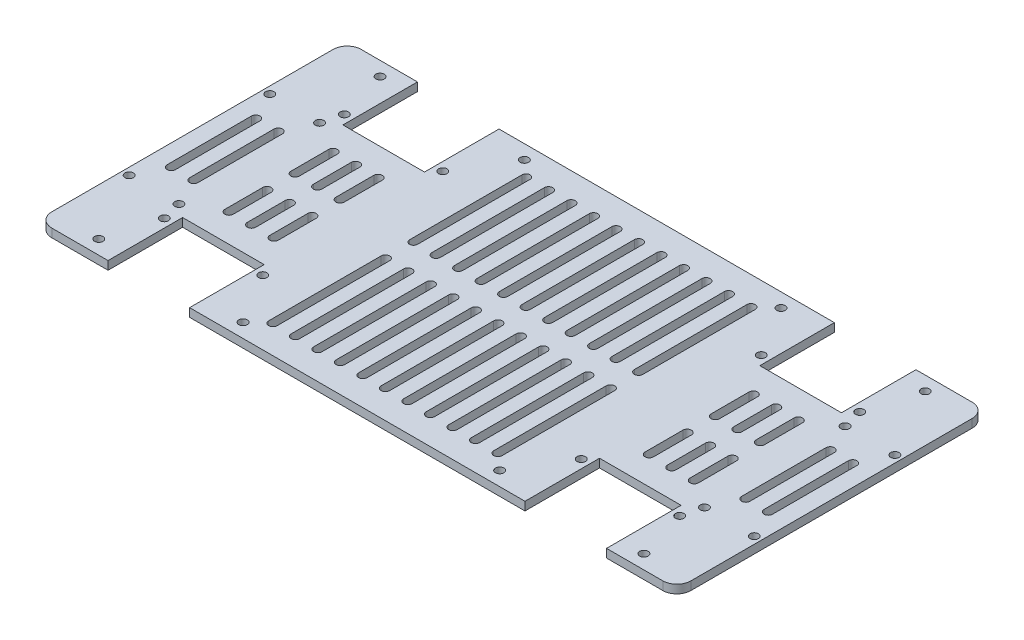
SolidWorks part; units mm, degrees
ref_plane "前视基准面" through (0, 0, 0) normal (0, 0, 1) x (1, 0, 0)
ref_plane "上视基准面" through (0, 0, 0) normal (0, 1, 0) x (1, 0, 0)
ref_plane "右视基准面" through (0, 0, 0) normal (1, 0, 0) x (0, 0, -1)
other "Configuration Table"
sketch "草图1" plane through (0, 0, 0) normal (0, 1, 0) x (1, 0, 0)
  line L5 (-51.0973, -171.2423) -> (-45.0973, -171.2423)
  line L6 (-45.0973, -171.2423) -> (-45.0973, -177.2423)
  line L7 (-45.0973, -177.2423) -> (-51.0973, -177.2423)
  line L8 (-80.0973, -171.2423) -> (-86.0973, -171.2423)
  line L12 (-86.0973, -171.2423) -> (-86.0973, -177.2423)
  line L13 (-86.0973, -177.2423) -> (-80.0973, -177.2423)
  line L14 (-80.0973, -113.2423) -> (-86.0973, -113.2423)
  line L37 (-88.3873, -92.2423) -> (105.4227, -92.2423) construction
  line L38 (105.4227, -92.2423) -> (105.4227, -192.2423) construction
  line L39 (105.4227, -192.2423) -> (-88.3873, -192.2423) construction
  line L40 (-88.3873, -192.2423) -> (-88.3873, -92.2423) construction
  line L42 (-105.0973, -197.2423) -> (122.1327, -197.2423)
  line L43 (122.1327, -197.2423) -> (122.1327, -87.2423)
  line L44 (122.1327, -87.2423) -> (-105.0973, -87.2423)
  line L46 (-105.0973, -87.2423) -> (-105.0973, -197.2423)
  line L48 (-80.0973, -87.2423) -> (-80.0973, -113.7423)
  line L49 (-80.0973, -113.7423) -> (-51.0973, -113.7423)
  line L50 (-51.0973, -113.7423) -> (-51.0973, -87.2423)
  line L52 (-80.0973, -197.2423) -> (-80.0973, -170.7423)
  line L53 (-80.0973, -170.7423) -> (-51.0973, -170.7423)
  line L54 (-51.0973, -170.7423) -> (-51.0973, -197.2423)
  line L56 (97.1327, -87.2423) -> (97.1327, -113.7423)
  line L57 (97.1327, -113.7423) -> (68.1327, -113.7423)
  line L58 (68.1327, -113.7423) -> (68.1327, -87.2423)
  line L60 (68.1327, -197.2423) -> (68.1327, -170.7423)
  line L61 (68.1327, -170.7423) -> (97.1327, -170.7423)
  line L62 (97.1327, -170.7423) -> (97.1327, -197.2423)
  line L63 (-86.0973, -113.2423) -> (-86.0973, -107.2423)
  line L64 (-86.0973, -107.2423) -> (-80.0973, -107.2423)
  line L66 (-51.0973, -107.2423) -> (-45.0973, -107.2423)
  line L67 (-45.0973, -107.2423) -> (-45.0973, -113.2423)
  line L68 (-45.0973, -113.2423) -> (-51.0973, -113.2423)
  line L70 (-86.0973, -110.2423) -> (-80.0973, -110.2423) construction
  line L72 (-83.0973, -107.2423) -> (-83.0973, -113.2423) construction
  line L73 (-51.0973, -110.2423) -> (-45.0973, -110.2423) construction
  line L74 (-48.0973, -107.2423) -> (-48.0973, -113.2423) construction
  line L75 (-86.0973, -174.2423) -> (-80.0973, -174.2423) construction
  line L76 (-83.0973, -171.2423) -> (-83.0973, -177.2423) construction
  line L77 (-48.0973, -171.2423) -> (-48.0973, -177.2423) construction
  line L78 (-45.0973, -174.2423) -> (-51.0973, -174.2423) construction
  line L79 (68.1327, -171.2423) -> (62.1327, -171.2423)
  line L80 (62.1327, -171.2423) -> (62.1327, -177.2423)
  line L81 (62.1327, -177.2423) -> (68.1327, -177.2423)
  line L82 (68.1327, -107.2423) -> (62.1327, -107.2423)
  line L83 (62.1327, -107.2423) -> (62.1327, -113.2423)
  line L84 (62.1327, -113.2423) -> (68.1327, -113.2423)
  line L85 (97.1327, -107.2423) -> (103.1327, -107.2423)
  line L86 (103.1327, -107.2423) -> (103.1327, -113.2423)
  line L87 (103.1327, -113.2423) -> (97.1327, -113.2423)
  line L88 (97.1327, -171.2423) -> (103.1327, -171.2423)
  line L89 (103.1327, -171.2423) -> (103.1327, -177.2423)
  line L90 (103.1327, -177.2423) -> (97.1327, -177.2423)
  line L91 (65.1327, -107.2423) -> (65.1327, -113.2423) construction
  line L92 (62.1327, -110.2423) -> (68.1327, -110.2423) construction
  line L93 (97.1327, -110.2423) -> (103.1327, -110.2423) construction
  line L94 (100.1327, -107.2423) -> (100.1327, -113.2423) construction
  line L95 (62.1327, -174.2423) -> (68.1327, -174.2423) construction
  line L96 (65.1327, -171.2423) -> (65.1327, -177.2423) construction
  line L97 (97.1327, -174.2423) -> (103.1327, -174.2423) construction
  line L98 (100.1327, -171.2423) -> (100.1327, -177.2423) construction
  line L99 (-105.0973, -142.2423) -> (122.1327, -142.2423) construction
  line L100 (8.5177, -87.2423) -> (8.5177, -197.2423) construction
  line L101 (8.5177, -97.2423) -> (8.5177, -137.2423) construction
  line L104 (10.0177, -97.2423) -> (10.0177, -137.2423)
  line L107 (7.0177, -97.2423) -> (7.0177, -137.2423)
  line L110 (8.5177, -147.2423) -> (8.5177, -187.2423) construction
  line L113 (10.0177, -147.2423) -> (10.0177, -187.2423)
  line L114 (7.0177, -147.2423) -> (7.0177, -187.2423)
  line L115 (16.5177, -97.2423) -> (16.5177, -137.2423) construction
  line L116 (18.0177, -97.2423) -> (18.0177, -137.2423)
  line L117 (15.0177, -97.2423) -> (15.0177, -137.2423)
  line L118 (16.5177, -147.2423) -> (16.5177, -187.2423) construction
  line L119 (18.0177, -147.2423) -> (18.0177, -187.2423)
  line L120 (15.0177, -147.2423) -> (15.0177, -187.2423)
  line L121 (24.5177, -97.2423) -> (24.5177, -137.2423) construction
  line L122 (26.0177, -97.2423) -> (26.0177, -137.2423)
  line L123 (23.0177, -97.2423) -> (23.0177, -137.2423)
  line L124 (24.5177, -147.2423) -> (24.5177, -187.2423) construction
  line L125 (26.0177, -147.2423) -> (26.0177, -187.2423)
  line L126 (23.0177, -147.2423) -> (23.0177, -187.2423)
  line L127 (32.5177, -97.2423) -> (32.5177, -137.2423) construction
  line L128 (34.0177, -97.2423) -> (34.0177, -137.2423)
  line L129 (31.0177, -97.2423) -> (31.0177, -137.2423)
  line L130 (40.5177, -97.2423) -> (40.5177, -137.2423) construction
  line L131 (42.0177, -97.2423) -> (42.0177, -137.2423)
  line L132 (39.0177, -97.2423) -> (39.0177, -137.2423)
  line L133 (32.5177, -147.2423) -> (32.5177, -187.2423) construction
  line L136 (40.5177, -147.2423) -> (40.5177, -187.2423) construction
  line L137 (42.0177, -147.2423) -> (42.0177, -187.2423)
  line L138 (39.0177, -147.2423) -> (39.0177, -187.2423)
  line L139 (34.0177, -147.2423) -> (34.0177, -187.2423)
  line L140 (31.0177, -147.2423) -> (31.0177, -187.2423)
  line L141 (0.5177, -97.2423) -> (0.5177, -137.2423) construction
  line L142 (2.0177, -97.2423) -> (2.0177, -137.2423)
  line L143 (-0.9823, -97.2423) -> (-0.9823, -137.2423)
  line L144 (-7.4823, -97.2423) -> (-7.4823, -137.2423) construction
  line L145 (-5.9823, -97.2423) -> (-5.9823, -137.2423)
  line L146 (-8.9823, -97.2423) -> (-8.9823, -137.2423)
  line L147 (-15.4823, -97.2423) -> (-15.4823, -137.2423) construction
  line L148 (-13.9823, -97.2423) -> (-13.9823, -137.2423)
  line L149 (-16.9823, -97.2423) -> (-16.9823, -137.2423)
  line L150 (-23.4823, -97.2423) -> (-23.4823, -137.2423) construction
  line L151 (-21.9823, -97.2423) -> (-21.9823, -137.2423)
  line L152 (-24.9823, -97.2423) -> (-24.9823, -137.2423)
  line L153 (0.5177, -147.2423) -> (0.5177, -187.2423) construction
  line L154 (2.0177, -147.2423) -> (2.0177, -187.2423)
  line L155 (-0.9823, -147.2423) -> (-0.9823, -187.2423)
  line L156 (-7.4823, -147.2423) -> (-7.4823, -187.2423) construction
  line L157 (-5.9823, -147.2423) -> (-5.9823, -187.2423)
  line L158 (-8.9823, -147.2423) -> (-8.9823, -187.2423)
  line L159 (-15.4823, -147.2423) -> (-15.4823, -187.2423) construction
  line L160 (-13.9823, -147.2423) -> (-13.9823, -187.2423)
  line L161 (-16.9823, -147.2423) -> (-16.9823, -187.2423)
  line L162 (-23.4823, -147.2423) -> (-23.4823, -187.2423) construction
  line L163 (-21.9823, -147.2423) -> (-21.9823, -187.2423)
  line L164 (-24.9823, -147.2423) -> (-24.9823, -187.2423)
  line L165 (-102.5973, -117.2423) -> (-102.5973, -167.2423) construction
  line L166 (-84.8973, -117.2423) -> (-84.8973, -167.2423) construction
  line L167 (119.6327, -117.2423) -> (119.6327, -167.2423) construction
  line L168 (119.6327, -167.2423) -> (101.9327, -167.2423) construction
  line L169 (101.9327, -167.2423) -> (101.9327, -117.2423) construction
  line L170 (101.9327, -117.2423) -> (119.6327, -117.2423) construction
  line L171 (-31.4823, -97.2423) -> (-31.4823, -137.2423) construction
  line L172 (-30.0652, -97.2423) -> (-30.0652, -137.2423)
  line L173 (-32.8995, -97.2423) -> (-32.8995, -137.2423)
  line L174 (-31.4823, -147.2423) -> (-31.4823, -187.2423) construction
  line L175 (-29.9823, -147.2423) -> (-29.9823, -187.2423)
  line L176 (-32.9823, -147.2423) -> (-32.9823, -187.2423)
  line L177 (48.5177, -97.2423) -> (48.5177, -137.2423) construction
  line L178 (50.0177, -97.2423) -> (50.0177, -137.2423)
  line L179 (47.0177, -97.2423) -> (47.0177, -137.2423)
  line L180 (48.5177, -147.2423) -> (48.5177, -187.2423) construction
  line L181 (50.0177, -147.2423) -> (50.0177, -187.2423)
  line L182 (47.0177, -147.2423) -> (47.0177, -187.2423)
  line L183 (-57.5973, -147.2423) -> (-57.5973, -160.7423) construction
  line L186 (-56.0973, -147.2423) -> (-56.0973, -160.7423)
  line L189 (-59.0973, -147.2423) -> (-59.0973, -160.7423)
  line L190 (-97.5973, -127.2423) -> (-97.5973, -157.2423) construction
  line L191 (-96.0973, -127.2423) -> (-96.0973, -157.2423)
  line L192 (-99.0973, -127.2423) -> (-99.0973, -157.2423)
  line L193 (-89.5973, -127.2423) -> (-89.5973, -157.2423) construction
  line L194 (-88.0973, -127.2423) -> (-88.0973, -157.2423)
  line L195 (-91.0973, -127.2423) -> (-91.0973, -157.2423)
  line L196 (-65.5973, -147.2423) -> (-65.5973, -160.7423) construction
  line L197 (-64.0973, -147.2423) -> (-64.0973, -160.7423)
  line L198 (-67.0973, -147.2423) -> (-67.0973, -160.7423)
  line L199 (-73.5973, -147.2423) -> (-73.5973, -160.7423) construction
  line L200 (-72.0973, -147.2423) -> (-72.0973, -160.7423)
  line L201 (-75.0973, -147.2423) -> (-75.0973, -160.7423)
  line L202 (-73.5973, -137.2423) -> (-73.5973, -123.7423) construction
  line L203 (-75.0973, -137.2423) -> (-75.0973, -123.7423)
  line L204 (-72.0973, -137.2423) -> (-72.0973, -123.7423)
  line L205 (-65.5973, -137.2423) -> (-65.5973, -123.7423) construction
  line L206 (-67.0973, -137.2423) -> (-67.0973, -123.7423)
  line L207 (-64.0973, -137.2423) -> (-64.0973, -123.7423)
  line L208 (-57.5973, -137.2423) -> (-57.5973, -123.7423) construction
  line L209 (-59.0973, -137.2423) -> (-59.0973, -123.7423)
  line L210 (-56.0973, -137.2423) -> (-56.0973, -123.7423)
  line L211 (114.6327, -127.2423) -> (114.6327, -157.2423) construction
  line L212 (116.1327, -127.2423) -> (116.1327, -157.2423)
  line L213 (113.1327, -127.2423) -> (113.1327, -157.2423)
  line L214 (106.6327, -127.2423) -> (106.6327, -157.2423) construction
  line L215 (108.1327, -127.2423) -> (108.1327, -157.2423)
  line L216 (105.1327, -127.2423) -> (105.1327, -157.2423)
  line L217 (83.8086, -123.7423) -> (83.8086, -137.2423) construction
  line L218 (85.3086, -123.7423) -> (85.3086, -137.2423)
  line L219 (82.3086, -123.7423) -> (82.3086, -137.2423)
  line L220 (83.8086, -147.2423) -> (83.8086, -160.7423) construction
  line L221 (85.3086, -147.2423) -> (85.3086, -160.7423)
  line L222 (82.3086, -147.2423) -> (82.3086, -160.7423)
  line L223 (75.8086, -123.7423) -> (75.8086, -137.2423) construction
  line L224 (77.3086, -123.7423) -> (77.3086, -137.2423)
  line L225 (74.3086, -123.7423) -> (74.3086, -137.2423)
  line L226 (75.8086, -147.2423) -> (75.8086, -160.7423) construction
  line L227 (77.3086, -147.2423) -> (77.3086, -160.7423)
  line L228 (74.3086, -147.2423) -> (74.3086, -160.7423)
  line L229 (91.8086, -123.7423) -> (91.8086, -137.2423) construction
  line L230 (93.3086, -123.7423) -> (93.3086, -137.2423)
  line L231 (90.3086, -123.7423) -> (90.3086, -137.2423)
  line L232 (91.8086, -147.2423) -> (91.8086, -160.7423) construction
  line L233 (93.3086, -147.2423) -> (93.3086, -160.7423)
  line L234 (90.3086, -147.2423) -> (90.3086, -160.7423)
  circle A9 centre (-88.3873, -92.2423) radius 1.5
  circle A10 centre (105.4227, -92.2423) radius 1.5
  circle A11 centre (105.4227, -192.2423) radius 1.5
  circle A12 centre (-88.3873, -192.2423) radius 1.5
  circle A13 centre (-37.0973, -92.2423) radius 1.5
  circle A14 centre (-37.0973, -192.2423) radius 1.5
  circle A15 centre (54.1327, -192.2423) radius 1.5
  circle A16 centre (54.1327, -92.2423) radius 1.5
  circle A17 centre (-83.0973, -110.2423) radius 1.5
  circle A18 centre (-48.0973, -110.2423) radius 1.5
  circle A19 centre (-83.0973, -174.2423) radius 1.5
  circle A20 centre (-48.0973, -174.2423) radius 1.5
  circle A21 centre (65.1327, -110.2423) radius 1.5
  circle A22 centre (100.1327, -110.2423) radius 1.5
  circle A23 centre (65.1327, -174.2423) radius 1.5
  circle A24 centre (100.1327, -174.2423) radius 1.5
  arc A33 (10.0177, -97.2423) -> (7.0177, -97.2423) centre (8.5177, -97.2423) ccw
  arc A34 (7.0177, -137.2423) -> (10.0177, -137.2423) centre (8.5177, -137.2423) ccw
  arc A35 (10.0177, -147.2423) -> (7.0177, -147.2423) centre (8.5177, -147.2423) ccw
  arc A36 (7.0177, -187.2423) -> (10.0177, -187.2423) centre (8.5177, -187.2423) ccw
  arc A37 (18.0177, -97.2423) -> (15.0177, -97.2423) centre (16.5177, -97.2423) ccw
  arc A38 (15.0177, -137.2423) -> (18.0177, -137.2423) centre (16.5177, -137.2423) ccw
  arc A39 (18.0177, -147.2423) -> (15.0177, -147.2423) centre (16.5177, -147.2423) ccw
  arc A40 (15.0177, -187.2423) -> (18.0177, -187.2423) centre (16.5177, -187.2423) ccw
  arc A41 (26.0177, -97.2423) -> (23.0177, -97.2423) centre (24.5177, -97.2423) ccw
  arc A42 (23.0177, -137.2423) -> (26.0177, -137.2423) centre (24.5177, -137.2423) ccw
  arc A43 (26.0177, -147.2423) -> (23.0177, -147.2423) centre (24.5177, -147.2423) ccw
  arc A44 (23.0177, -187.2423) -> (26.0177, -187.2423) centre (24.5177, -187.2423) ccw
  arc A45 (34.0177, -97.2423) -> (31.0177, -97.2423) centre (32.5177, -97.2423) ccw
  arc A46 (31.0177, -137.2423) -> (34.0177, -137.2423) centre (32.5177, -137.2423) ccw
  arc A47 (42.0177, -97.2423) -> (39.0177, -97.2423) centre (40.5177, -97.2423) ccw
  arc A48 (39.0177, -137.2423) -> (42.0177, -137.2423) centre (40.5177, -137.2423) ccw
  arc A51 (42.0177, -147.2423) -> (39.0177, -147.2423) centre (40.5177, -147.2423) ccw
  arc A52 (39.0177, -187.2423) -> (42.0177, -187.2423) centre (40.5177, -187.2423) ccw
  arc A53 (34.0177, -147.2423) -> (31.0177, -147.2423) centre (32.5177, -147.2423) ccw
  arc A54 (31.0177, -187.2423) -> (34.0177, -187.2423) centre (32.5177, -187.2423) ccw
  arc A55 (2.0177, -97.2423) -> (-0.9823, -97.2423) centre (0.5177, -97.2423) ccw
  arc A56 (-0.9823, -137.2423) -> (2.0177, -137.2423) centre (0.5177, -137.2423) ccw
  arc A57 (-5.9823, -97.2423) -> (-8.9823, -97.2423) centre (-7.4823, -97.2423) ccw
  arc A58 (-8.9823, -137.2423) -> (-5.9823, -137.2423) centre (-7.4823, -137.2423) ccw
  arc A59 (-13.9823, -97.2423) -> (-16.9823, -97.2423) centre (-15.4823, -97.2423) ccw
  arc A60 (-16.9823, -137.2423) -> (-13.9823, -137.2423) centre (-15.4823, -137.2423) ccw
  arc A61 (-21.9823, -97.2423) -> (-24.9823, -97.2423) centre (-23.4823, -97.2423) ccw
  arc A62 (-24.9823, -137.2423) -> (-21.9823, -137.2423) centre (-23.4823, -137.2423) ccw
  arc A63 (2.0177, -147.2423) -> (-0.9823, -147.2423) centre (0.5177, -147.2423) ccw
  arc A64 (-0.9823, -187.2423) -> (2.0177, -187.2423) centre (0.5177, -187.2423) ccw
  arc A65 (-5.9823, -147.2423) -> (-8.9823, -147.2423) centre (-7.4823, -147.2423) ccw
  arc A66 (-8.9823, -187.2423) -> (-5.9823, -187.2423) centre (-7.4823, -187.2423) ccw
  arc A67 (-13.9823, -147.2423) -> (-16.9823, -147.2423) centre (-15.4823, -147.2423) ccw
  arc A68 (-16.9823, -187.2423) -> (-13.9823, -187.2423) centre (-15.4823, -187.2423) ccw
  arc A69 (-21.9823, -147.2423) -> (-24.9823, -147.2423) centre (-23.4823, -147.2423) ccw
  arc A70 (-24.9823, -187.2423) -> (-21.9823, -187.2423) centre (-23.4823, -187.2423) ccw
  circle A71 centre (-102.5973, -117.2423) radius 1.5
  circle A72 centre (-102.5973, -167.2423) radius 1.5
  circle A73 centre (-84.8973, -117.2423) radius 1.5
  circle A74 centre (-84.8973, -167.2423) radius 1.5
  circle A75 centre (119.6327, -117.2423) radius 1.5
  circle A76 centre (119.6327, -167.2423) radius 1.5
  circle A78 centre (101.9327, -117.2423) radius 1.5
  circle A79 centre (101.9327, -167.2423) radius 1.5
  arc A80 (-30.0652, -97.2423) -> (-32.8995, -97.2423) centre (-31.4823, -97.2423) ccw
  arc A81 (-32.8995, -137.2423) -> (-30.0652, -137.2423) centre (-31.4823, -137.2423) ccw
  arc A82 (-29.9823, -147.2423) -> (-32.9823, -147.2423) centre (-31.4823, -147.2423) ccw
  arc A83 (-32.9823, -187.2423) -> (-29.9823, -187.2423) centre (-31.4823, -187.2423) ccw
  arc A84 (50.0177, -97.2423) -> (47.0177, -97.2423) centre (48.5177, -97.2423) ccw
  arc A85 (47.0177, -137.2423) -> (50.0177, -137.2423) centre (48.5177, -137.2423) ccw
  arc A86 (50.0177, -147.2423) -> (47.0177, -147.2423) centre (48.5177, -147.2423) ccw
  arc A87 (47.0177, -187.2423) -> (50.0177, -187.2423) centre (48.5177, -187.2423) ccw
  arc A98 (-56.0973, -147.2423) -> (-59.0973, -147.2423) centre (-57.5973, -147.2423) ccw
  arc A99 (-59.0973, -160.7423) -> (-56.0973, -160.7423) centre (-57.5973, -160.7423) ccw
  arc A100 (-96.0973, -127.2423) -> (-99.0973, -127.2423) centre (-97.5973, -127.2423) ccw
  arc A101 (-99.0973, -157.2423) -> (-96.0973, -157.2423) centre (-97.5973, -157.2423) ccw
  arc A102 (-88.0973, -127.2423) -> (-91.0973, -127.2423) centre (-89.5973, -127.2423) ccw
  arc A103 (-91.0973, -157.2423) -> (-88.0973, -157.2423) centre (-89.5973, -157.2423) ccw
  arc A104 (-64.0973, -147.2423) -> (-67.0973, -147.2423) centre (-65.5973, -147.2423) ccw
  arc A105 (-67.0973, -160.7423) -> (-64.0973, -160.7423) centre (-65.5973, -160.7423) ccw
  arc A106 (-72.0973, -147.2423) -> (-75.0973, -147.2423) centre (-73.5973, -147.2423) ccw
  arc A107 (-75.0973, -160.7423) -> (-72.0973, -160.7423) centre (-73.5973, -160.7423) ccw
  arc A108 (-75.0973, -137.2423) -> (-72.0973, -137.2423) centre (-73.5973, -137.2423) ccw
  arc A109 (-72.0973, -123.7423) -> (-75.0973, -123.7423) centre (-73.5973, -123.7423) ccw
  arc A110 (-67.0973, -137.2423) -> (-64.0973, -137.2423) centre (-65.5973, -137.2423) ccw
  arc A111 (-64.0973, -123.7423) -> (-67.0973, -123.7423) centre (-65.5973, -123.7423) ccw
  arc A112 (-59.0973, -137.2423) -> (-56.0973, -137.2423) centre (-57.5973, -137.2423) ccw
  arc A113 (-56.0973, -123.7423) -> (-59.0973, -123.7423) centre (-57.5973, -123.7423) ccw
  arc A114 (116.1327, -127.2423) -> (113.1327, -127.2423) centre (114.6327, -127.2423) ccw
  arc A115 (113.1327, -157.2423) -> (116.1327, -157.2423) centre (114.6327, -157.2423) ccw
  arc A116 (108.1327, -127.2423) -> (105.1327, -127.2423) centre (106.6327, -127.2423) ccw
  arc A117 (105.1327, -157.2423) -> (108.1327, -157.2423) centre (106.6327, -157.2423) ccw
  arc A118 (85.3086, -123.7423) -> (82.3086, -123.7423) centre (83.8086, -123.7423) ccw
  arc A119 (82.3086, -137.2423) -> (85.3086, -137.2423) centre (83.8086, -137.2423) ccw
  arc A120 (85.3086, -147.2423) -> (82.3086, -147.2423) centre (83.8086, -147.2423) ccw
  arc A121 (82.3086, -160.7423) -> (85.3086, -160.7423) centre (83.8086, -160.7423) ccw
  arc A122 (77.3086, -123.7423) -> (74.3086, -123.7423) centre (75.8086, -123.7423) ccw
  arc A123 (74.3086, -137.2423) -> (77.3086, -137.2423) centre (75.8086, -137.2423) ccw
  arc A124 (77.3086, -147.2423) -> (74.3086, -147.2423) centre (75.8086, -147.2423) ccw
  arc A125 (74.3086, -160.7423) -> (77.3086, -160.7423) centre (75.8086, -160.7423) ccw
  arc A126 (93.3086, -123.7423) -> (90.3086, -123.7423) centre (91.8086, -123.7423) ccw
  arc A127 (90.3086, -137.2423) -> (93.3086, -137.2423) centre (91.8086, -137.2423) ccw
  arc A128 (93.3086, -147.2423) -> (90.3086, -147.2423) centre (91.8086, -147.2423) ccw
  arc A129 (90.3086, -160.7423) -> (93.3086, -160.7423) centre (91.8086, -160.7423) ccw
  point P13 (-45.0973, -110.2423)
  point P124 (8.5177, -117.2423)
  point P129 (8.5177, -167.2423)
  point P138 (16.5177, -117.2423)
  point P143 (16.5177, -167.2423)
  point P150 (24.5177, -117.2423)
  point P157 (24.5177, -167.2423)
  point P166 (32.5177, -117.2423)
  point P171 (40.5177, -117.2423)
  point P180 (32.5177, -167.2423)
  point P186 (40.5177, -167.2423)
  point P191 (0.5177, -117.2423)
  point P198 (-7.4823, -117.2423)
  point P205 (-15.4823, -117.2423)
  point P212 (-23.4823, -117.2423)
  point P221 (0.5177, -167.2423)
  point P226 (-7.4823, -167.2423)
  point P233 (-15.4823, -167.2423)
  point P240 (-23.4823, -167.2423)
  point P265 (-31.4823, -117.2423)
  point P270 (-31.4823, -167.2423)
  point P277 (48.5177, -117.2423)
  point P284 (48.5177, -167.2423)
  point P293 (-57.5973, -153.9923)
  point P300 (-97.5973, -142.2423)
  point P307 (-89.5973, -142.2423)
  point P314 (-65.5973, -153.9923)
  point P319 (-73.5973, -153.9923)
  point P326 (-73.5973, -130.4923)
  point P333 (-65.5973, -130.4923)
  point P340 (-57.5973, -130.4923)
  point P347 (114.6327, -142.2423)
  point P354 (106.6327, -142.2423)
  point P363 (83.8086, -130.4923)
  point P368 (83.8086, -153.9923)
  point P375 (75.8086, -130.4923)
  point P382 (75.8086, -153.9923)
  point P389 (91.8086, -130.4923)
  point P396 (91.8086, -153.9923)
  point P403 (65.1327, -174.2423)
  dimension "D23" = 3
  dimension "D24" = 3
  dimension "D27" = 5
  dimension "D30" = 3
  dimension "D35" = 3
  dimension "D11" = 3
  dimension "D13" = 3
  dimension "D16" = 6
  dimension "D36" = 3
  dimension "D38" = 3
  dimension "D39" = 3
  dimension "D51" = 3
  dimension "D54" = 3
  dimension "D56" = 3
  dimension "D58" = 3
  dimension "D12" = 3
  dimension "D14" = 3
  dimension "D20" = 3
  dimension "D21" = 3
  dimension "D22" = 3
  dimension "D80" = 3
  dimension "D81" = 3
  dimension "D84" = 3
  dimension "D85" = 3
  dimension "D88" = 3
  dimension "D89" = 3
  dimension "D90" = 3
  dimension "D91" = 3
  dimension "D1" = 20
  dimension "D2" = 6
  dimension "D6" = 6
  dimension "D7" = 6
  dimension "D8" = 20
  dimension "D9" = 6
  dimension "D10" = 6
  dimension "D15" = 6
  dimension "D17" = 6
  dimension "D18" = 6
  dimension "D19" = 6
  dimension "D25" = 5
  dimension "D26" = 3
  dimension "D28" = 10
  dimension "D29" = 10
  dimension "D31" = 193.81
  dimension "D32" = 3
  dimension "D33" = 3
  dimension "D34" = 3
  dimension "D37" = 8
  dimension "D40" = 110
  dimension "D41" = 5
  dimension "D42" = 5
  dimension "D43" = 16.71
  dimension "D44" = 16.71
  dimension "D45" = 25
  dimension "D46" = 29
  dimension "D47" = 26.5
  dimension "D48" = 26.5
  dimension "D49" = 29
  dimension "D50" = 25
  dimension "D52" = 14
  dimension "D53" = 8
  dimension "D55" = 14
  dimension "D57" = 14
  dimension "D59" = 14
  dimension "D60" = 3
  dimension "D61" = 3
  dimension "D62" = 3
  dimension "D63" = 3
  dimension "D64" = 8
  dimension "D65" = 8
  dimension "D66" = 3
  dimension "D67" = 3
  dimension "D68" = 3
  dimension "D69" = 3
  dimension "D70" = 8
  dimension "D71" = 8
  dimension "D72" = 8
  dimension "D73" = 8
  dimension "D74" = 3
  dimension "D75" = 3
  dimension "D76" = 3
  dimension "D77" = 3
  dimension "D78" = 25
  dimension "D79" = 25
  dimension "D82" = 2.5
  dimension "D83" = 17.7
  dimension "D86" = 17.7
  dimension "D87" = 2.5
  dimension "D92" = 25
  dimension "D93" = 25
  dimension "D94" = 10
  dimension "D95" = 5
  dimension "D96" = 8
  dimension "D97" = 3
  dimension "D98" = 14.5
  dimension "D99" = 8
  dimension "D100" = 3
  dimension "D101" = 3
  dimension "D102" = 3
  dimension "D103" = 3
  dimension "D104" = 7.5
  dimension "D105" = 15
  dimension "D106" = 15
  dimension "D107" = 3
  dimension "D108" = 8
  dimension "D109" = 3
  dimension "D110" = 3
  dimension "D111" = 3
  dimension "D112" = 3
  dimension "D113" = 3
  dimension "D114" = 10
  dimension "D115" = 5
  dimension "D116" = 8
  dimension "D117" = 8
  dimension "D118" = 8
  dimension "D119" = 3
  dimension "D120" = 3
  dimension "D121" = 7.5
  dimension "D122" = 8
  dimension "D123" = 15
  dimension "D124" = 15
  dimension "D125" = 15
  dimension "D126" = 15
  dimension "D127" = 3
  dimension "D128" = 3
  dimension "D129" = 3
  dimension "D130" = 3
  dimension "D131" = 3
  dimension "D132" = 3
  dimension "D133" = 5
  dimension "D134" = 10
  dimension "D135" = 5
  dimension "D136" = 10
  dimension "D137" = 8
  dimension "D138" = 8
  dimension "D139" = 90
  dimension "D140" = 6
extrude "凸台-拉伸2" add sketch "草图1" along normal blind 3 contours L61 L62 L42 L43 L44 L56 L57 L58 L50 L49 L48 L46 L52 L53 L54 L60 A16 A15 A14 A13 A12 A11 A10 A9 | L64 L63 L14 L48 A17 | L68 L67 L66 L50 A18 | L13 L52 L8 L12 A19 | L5 L54 L7 L6 A20 | L83 L84 L58 L82 A21 | L80 L81 L60 L79 A23 | L90 L89 L88 L62 A24 | L87 L86 L85 L56 A22
fillet "圆角1" radius 5 4 edges at (122.1327, 1.5, 87.2423) (122.1327, 1.5, 197.2423) (-105.0973, 1.5, 197.2423) (-105.0973, 1.5, 87.2423)
